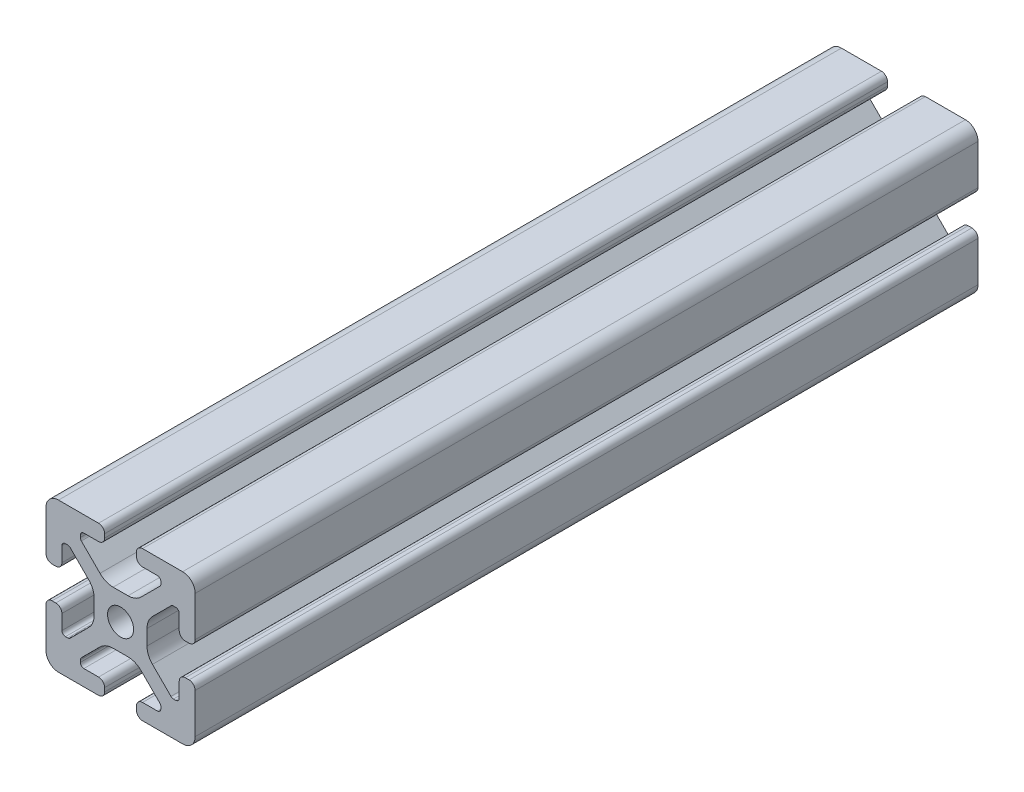
SolidWorks part; units mm, degrees
ref_plane "Front Plane" through (0, 0, 0) normal (0, 0, 1) x (1, 0, 0)
ref_plane "Top Plane" through (0, 0, 0) normal (0, 1, 0) x (1, 0, 0)
ref_plane "Right Plane" through (0, 0, 0) normal (1, 0, 0) x (0, 0, -1)
sketch "Sketch1" plane through (0, 0, 0) normal (0, 0, 1) x (1, 0, 0)
  line L0 (-10.287, 13.5524) -> (-10.287, 14.0843)
  line L1 (-9.3853, 14.986) -> (-5.6176, 14.986)
  line L2 (-4.064, 16.5396) -> (-4.064, 17.4964)
  line L3 (-5.6176, 19.05) -> (-7.9742, 19.05)
  line L4 (-7.9742, 19.05) -> (-15.8475, 19.05)
  line L5 (-19.05, 15.8475) -> (-19.05, 7.9763)
  line L6 (-19.05, 7.9763) -> (-19.05, 5.6176)
  line L7 (-17.4964, 4.064) -> (-16.5396, 4.064)
  line L8 (-14.986, 5.6176) -> (-14.986, 9.3853)
  line L9 (-14.0843, 10.287) -> (-13.516, 10.287)
  line L10 (-12.8784, 10.0229) -> (-8.1476, 5.2921)
  line L11 (-6.7564, 1.9335) -> (-6.7564, -1.9335)
  line L12 (-8.1476, -5.2921) -> (-12.8784, -10.0229)
  line L13 (-13.516, -10.287) -> (-14.0843, -10.287)
  line L14 (-14.986, -9.3853) -> (-14.986, -5.6176)
  line L15 (-16.5396, -4.064) -> (-17.4964, -4.064)
  line L16 (-19.05, -5.6176) -> (-19.05, -7.9763)
  line L17 (-19.05, -7.9763) -> (-19.05, -15.8475)
  line L18 (-15.8475, -19.05) -> (-7.9763, -19.05)
  line L19 (-7.9763, -19.05) -> (-5.6176, -19.05)
  line L20 (-4.064, -17.4964) -> (-4.064, -16.5396)
  line L21 (-5.6176, -14.986) -> (-9.3853, -14.986)
  line L22 (-10.287, -14.0843) -> (-10.287, -13.5524)
  line L23 (-10.0229, -12.9148) -> (-5.2522, -8.144)
  line L24 (-1.9022, -6.7564) -> (1.9022, -6.7564)
  line L25 (5.2522, -8.144) -> (10.0229, -12.9148)
  line L26 (10.287, -13.5524) -> (10.287, -14.0843)
  line L27 (9.3853, -14.986) -> (5.6176, -14.986)
  line L28 (4.064, -16.5396) -> (4.064, -17.4964)
  line L29 (5.6176, -19.05) -> (7.9763, -19.05)
  line L30 (7.9763, -19.05) -> (15.8475, -19.05)
  line L31 (19.05, -15.8475) -> (19.05, -7.9763)
  line L32 (19.05, -7.9763) -> (19.05, -5.6176)
  line L33 (17.4964, -4.064) -> (16.5396, -4.064)
  line L34 (14.986, -5.6176) -> (14.986, -9.3853)
  line L35 (14.0843, -10.287) -> (13.516, -10.287)
  line L36 (12.8784, -10.0229) -> (8.1476, -5.2921)
  line L37 (6.7564, -1.9335) -> (6.7564, 1.9335)
  line L38 (8.1476, 5.2921) -> (12.8784, 10.0229)
  line L39 (13.516, 10.287) -> (14.0843, 10.287)
  line L40 (14.986, 9.3853) -> (14.986, 5.6176)
  line L41 (16.5396, 4.064) -> (17.4964, 4.064)
  line L42 (19.05, 5.6176) -> (19.05, 9.4961)
  line L43 (19.05, 9.4961) -> (19.05, 15.8475)
  line L44 (15.8475, 19.05) -> (7.9742, 19.05)
  line L45 (7.9742, 19.05) -> (5.6176, 19.05)
  line L46 (4.064, 17.4964) -> (4.064, 16.5396)
  line L47 (5.6176, 14.986) -> (9.3853, 14.986)
  line L48 (10.287, 14.0843) -> (10.287, 13.5524)
  line L49 (10.0229, 12.9148) -> (5.2522, 8.144)
  line L50 (1.9022, 6.7564) -> (-1.9022, 6.7564)
  line L51 (-5.2522, 8.144) -> (-10.0229, 12.9148)
  circle A0 centre (0, 0) radius 3.3274
  arc A1 (-9.3853, 14.986) -> (-10.287, 14.0843) centre (-9.3853, 14.0843) ccw
  arc A2 (-5.6176, 14.986) -> (-4.064, 16.5396) centre (-5.6176, 16.5396) ccw
  arc A3 (-4.064, 17.4964) -> (-5.6176, 19.05) centre (-5.6176, 17.4964) ccw
  arc A6 (-15.8475, 19.05) -> (-19.05, 15.8475) centre (-15.8751, 15.8751) ccw
  arc A9 (-19.05, 5.6176) -> (-17.4964, 4.064) centre (-17.4964, 5.6176) ccw
  arc A10 (-16.5396, 4.064) -> (-14.986, 5.6176) centre (-16.5396, 5.6176) ccw
  arc A11 (-14.0843, 10.287) -> (-14.986, 9.3853) centre (-14.0843, 9.3853) ccw
  arc A12 (-12.8784, 10.0229) -> (-13.516, 10.287) centre (-13.516, 9.3853) ccw
  arc A13 (-6.7564, 1.9335) -> (-8.1476, 5.2921) centre (-11.5062, 1.9335) ccw
  arc A14 (-8.1476, -5.2921) -> (-6.7564, -1.9335) centre (-11.5062, -1.9335) ccw
  arc A15 (-13.516, -10.287) -> (-12.8784, -10.0229) centre (-13.516, -9.3853) ccw
  arc A16 (-14.986, -9.3853) -> (-14.0843, -10.287) centre (-14.0843, -9.3853) ccw
  arc A17 (-14.986, -5.6176) -> (-16.5396, -4.064) centre (-16.5396, -5.6176) ccw
  arc A18 (-17.4964, -4.064) -> (-19.05, -5.6176) centre (-17.4964, -5.6176) ccw
  arc A21 (-19.05, -15.8475) -> (-15.8475, -19.05) centre (-15.8751, -15.8751) ccw
  arc A24 (-5.6176, -19.05) -> (-4.064, -17.4964) centre (-5.6176, -17.4964) ccw
  arc A25 (-4.064, -16.5396) -> (-5.6176, -14.986) centre (-5.6176, -16.5396) ccw
  arc A26 (-10.287, -14.0843) -> (-9.3853, -14.986) centre (-9.3853, -14.0843) ccw
  arc A27 (-10.0229, -12.9148) -> (-10.287, -13.5524) centre (-9.3853, -13.5524) ccw
  arc A28 (-1.9022, -6.7564) -> (-5.2522, -8.144) centre (-1.9022, -11.494) ccw
  arc A29 (5.2522, -8.144) -> (1.9022, -6.7564) centre (1.9022, -11.494) ccw
  arc A30 (10.287, -13.5524) -> (10.0229, -12.9148) centre (9.3853, -13.5524) ccw
  arc A31 (9.3853, -14.986) -> (10.287, -14.0843) centre (9.3853, -14.0843) ccw
  arc A32 (5.6176, -14.986) -> (4.064, -16.5396) centre (5.6176, -16.5396) ccw
  arc A33 (4.064, -17.4964) -> (5.6176, -19.05) centre (5.6176, -17.4964) ccw
  arc A36 (15.8475, -19.05) -> (19.05, -15.8475) centre (15.8751, -15.8751) ccw
  arc A39 (19.05, -5.6176) -> (17.4964, -4.064) centre (17.4964, -5.6176) ccw
  arc A40 (16.5396, -4.064) -> (14.986, -5.6176) centre (16.5396, -5.6176) ccw
  arc A41 (14.0843, -10.287) -> (14.986, -9.3853) centre (14.0843, -9.3853) ccw
  arc A42 (12.8784, -10.0229) -> (13.516, -10.287) centre (13.516, -9.3853) ccw
  arc A43 (6.7564, -1.9335) -> (8.1476, -5.2921) centre (11.5062, -1.9335) ccw
  arc A44 (8.1476, 5.2921) -> (6.7564, 1.9335) centre (11.5062, 1.9335) ccw
  arc A45 (13.516, 10.287) -> (12.8784, 10.0229) centre (13.516, 9.3853) ccw
  arc A46 (14.986, 9.3853) -> (14.0843, 10.287) centre (14.0843, 9.3853) ccw
  arc A47 (14.986, 5.6176) -> (16.5396, 4.064) centre (16.5396, 5.6176) ccw
  arc A48 (17.4964, 4.064) -> (19.05, 5.6176) centre (17.4964, 5.6176) ccw
  arc A51 (19.05, 15.8475) -> (15.8475, 19.05) centre (15.8751, 15.8751) ccw
  arc A54 (5.6176, 19.05) -> (4.064, 17.4964) centre (5.6176, 17.4964) ccw
  arc A55 (4.064, 16.5396) -> (5.6176, 14.986) centre (5.6176, 16.5396) ccw
  arc A56 (10.287, 14.0843) -> (9.3853, 14.986) centre (9.3853, 14.0843) ccw
  arc A57 (10.0229, 12.9148) -> (10.287, 13.5524) centre (9.3853, 13.5524) ccw
  arc A58 (1.9022, 6.7564) -> (5.2522, 8.144) centre (1.9022, 11.494) ccw
  arc A59 (-5.2522, 8.144) -> (-1.9022, 6.7564) centre (-1.9022, 11.494) ccw
  arc A60 (-10.287, 13.5524) -> (-10.0229, 12.9148) centre (-9.3853, 13.5524) ccw
extrude "Boss-Extrude1" add sketch "Sketch1" along normal mid plane 200
